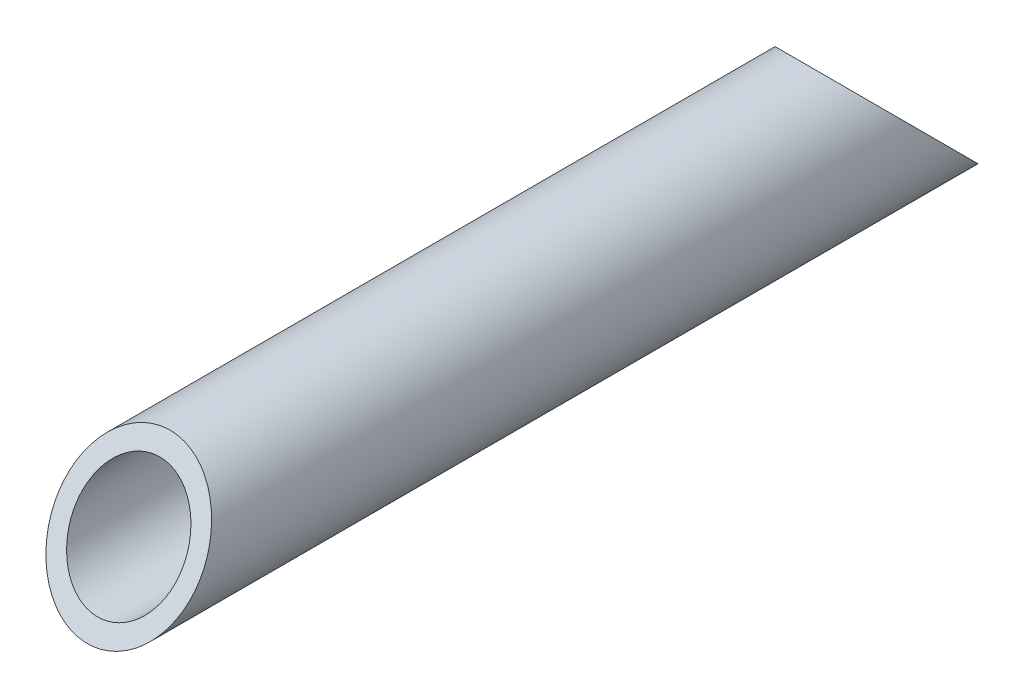
SolidWorks part; units mm, degrees
ref_plane "Front Plane" through (0, 0, 0) normal (0, 0, 1) x (1, 0, 0)
ref_plane "Top Plane" through (0, 0, 0) normal (0, 1, 0) x (1, 0, 0)
ref_plane "Right Plane" through (0, 0, 0) normal (1, 0, 0) x (0, 0, -1)
sketch "Sketch1" plane through (0, 0, 0) normal (0, 0, 1) x (1, 0, 0)
  circle A0 centre (0, 0) radius 6.35
  circle A1 centre (0, 0) radius 4.7625
  dimension "D1" = 12.7
  dimension "D2" = 9.525
extrude "Boss-Extrude1" add sketch "Sketch1" along normal blind 76.2
sketch "Sketch2" plane through (0, 0, 0) normal (1, 0, 0) x (0, 0, -1)
  line L0 (-76.2, -6.35) -> (-68.8677, 6.35)
  line L1 (0, 6.35) -> (-76.2, 6.35) construction
  line L2 (-68.8677, 6.35) -> (-76.2, 6.35)
  line L3 (-76.2, 6.35) -> (-76.2, -6.35)
  dimension "D1" = 60
extrude "Cut-Extrude1" cut sketch "Sketch2" against normal mid plane 76.2
sketch "Sketch3" plane through (0, 0, 0) normal (1, 0, 0) x (0, 0, -1)
  line L0 (-12.7, 6.35) -> (0, -6.35)
  line L1 (0, 6.35) -> (-68.8677, 6.35) construction
  line L2 (0, -6.35) -> (0, 6.35)
  line L3 (0, 6.35) -> (-12.7, 6.35)
  dimension "D1" = 45
extrude "Cut-Extrude3" cut sketch "Sketch3" against normal mid plane 76.2
ref_plane "Plane1" through (0, 6.35, 0) normal (0, 1, 0) x (1, 0, 0)
sketch "Sketch4" plane through (0, 31.4081, 54.4004) normal (0, 0.5, 0.866) x (1, 0, 0)
  line L0 (0, -43.5993) -> (-6.35, -43.5993) construction
  line L1 (0, -43.5993) -> (6.35, -43.5993) construction
  ellipse E0 centre (0, -36.2669) end of major axis (0, -28.9346) minor radius 6.35 construction
  point P8 (0, 0)
  point P10 (0, 0)
  point P11 (0.189, -41.2567)
  point P12 (6.35, -43.5993)
  dimension "D1" = 6.35
  dimension "D2" = 6.35
